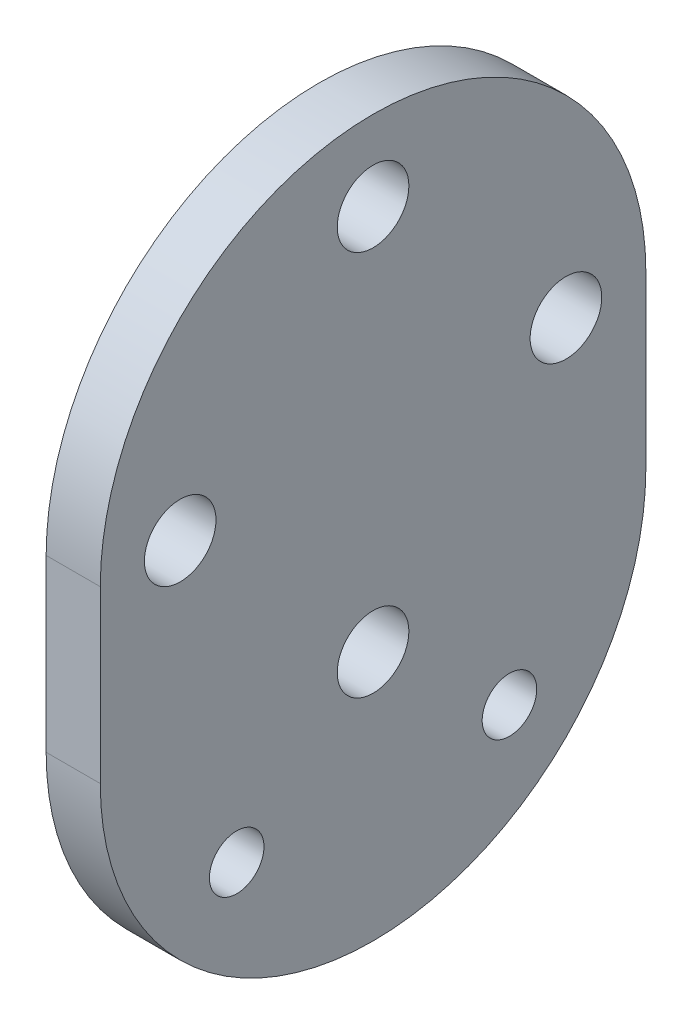
SolidWorks part; units mm, degrees
ref_plane "Front" through (0, 0, 0) normal (0, 0, 1) x (1, 0, 0)
ref_plane "Top" through (0, 0, 0) normal (0, 1, 0) x (1, 0, 0)
ref_plane "Right" through (0, 0, 0) normal (1, 0, 0) x (0, 0, -1)
sketch "Sketch2" plane through (0, 0, 0) normal (1, 0, 0) x (0, 0, -1)
  line L0 (0, -5) -> (0, 5) construction
  line L1 (-16, -5) -> (-16, 5)
  line L2 (16, -5) -> (16, 5)
  line L3 (0, -5) -> (8, -13)
  line L4 (0, -5) -> (20, -5) construction
  line L5 (0, 11) -> (20, 11)
  line L6 (0, -21) -> (20, -21)
  line L7 (20, -5) -> (28, 3)
  arc A0 (-16, -5) -> (16, -5) centre (0, -5) ccw
  arc A1 (16, 5) -> (-16, 5) centre (0, 5) ccw
  circle A2 centre (0, 5) radius 11.3137
  circle A3 centre (0, 16.3137) radius 2.1
  circle A4 centre (0, -6.3137) radius 2.1
  circle A5 centre (11.3137, 5) radius 2.1
  circle A6 centre (-11.3137, 5) radius 2.1
  circle A7 centre (0, -5) radius 11.3137
  circle A11 centre (8, -13) radius 1.6
  circle A12 centre (-8, -13) radius 1.6
  arc A13 (0, 11) -> (0, -21) centre (0, -5) ccw
  arc A14 (20, -21) -> (20, 11) centre (20, -5) ccw
  circle A15 centre (20, -5) radius 11.3137
  circle A16 centre (28, 3) radius 1.6
  circle A17 centre (28, -13) radius 1.6
  point P2 (0, 0)
  point P25 (10, -5)
  dimension "D1" = 16
  dimension "D2" = 22.6274
  dimension "D3" = 22.6274
extrude "Boss-Extrude1" add sketch "Sketch2" along normal blind 3.175 contours A15 A1 L5 A2 A5 | A13 A6 A2 A3 L5 A1 L1 | A13 L5 A2 A3 A6 | A15 A2 A5 L5 A13 A6 A7 | A15 A7 A2 A4 | A2 A15 A7 | A1 A15 A5 A2 A7 A0 L2 | A7 A15 A2 | A2 A15 A7 | A15 A5 A2 | A15 A2 A4 L3 A11 A7 | A12 A7 A11 L3 A4 A2 | A15 A7 A11 A12 A2 A6 A13 A0
